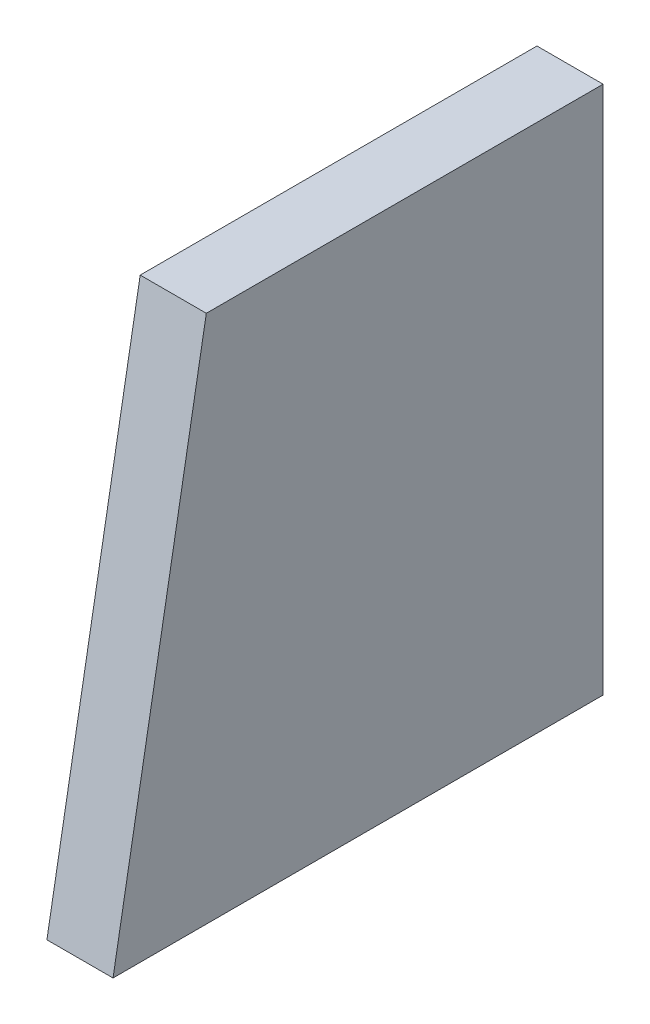
SolidWorks part; units mm, degrees
ref_plane "Front Plane" through (0, 0, 0) normal (0, 0, 1) x (1, 0, 0)
ref_plane "Top Plane" through (0, 0, 0) normal (0, 1, 0) x (1, 0, 0)
ref_plane "Right Plane" through (0, 0, 0) normal (1, 0, 0) x (0, 0, -1)
sketch "Sketch1" plane through (0, 0, 0) normal (1, 0, 0) x (0, 0, -1)
  line L0 (0, 0) -> (8.9574, 50.8)
  line L1 (8.9574, 50.8) -> (47.0574, 50.8)
  line L2 (47.0574, 50.8) -> (47.0574, 0)
  line L3 (47.0574, 0) -> (0, 0)
  dimension "D1" = 80
  dimension "D2" = 38.1
  dimension "D3" = 50.8
extrude "Boss-Extrude1" add sketch "Sketch1" along normal blind 6.35
